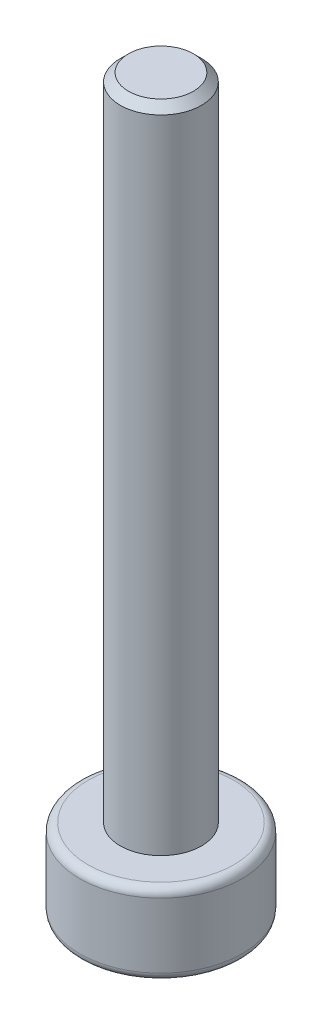
SolidWorks part; units mm, degrees
material "AISI 304"
ref_plane "前视基准面" through (0, 0, 0) normal (0, 0, 1) x (1, 0, 0)
ref_plane "上视基准面" through (0, 0, 0) normal (0, 1, 0) x (1, 0, 0)
ref_plane "右视基准面" through (0, 0, 0) normal (1, 0, 0) x (0, 0, -1)
sketch "草图2" plane through (0, 0, 0) normal (0, 1, 0) x (1, 0, 0)
  circle A0 centre (0, 0) radius 2
  dimension "D1" = 4
extrude "凸台-拉伸1" add sketch "草图2" along normal blind 2
sketch "草图3" plane through (0, 2, 0) normal (0, 1, 0) x (1, 0, 0)
  circle A0 centre (0, 0) radius 1
  dimension "D1" = 2
extrude "凸台-拉伸2" add sketch "草图3" along normal blind 16
fillet "圆角1" radius 0.2 2 edges at (0, 2, 2) (0, 0, 2)
sketch "草图4" plane through (0, 0, 0) normal (0, -1, 0) x (1, 0, 0)
  circle A0 centre (0, 0) radius 0.765
  dimension "D1" = 1.53
extrude "切除-拉伸1" cut sketch "草图4" against normal blind 1.52
chamfer "倒角1" distance 0.1 angle 45 1 edges at (0, 0, -0.765)
chamfer "倒角2" distance 0.2 angle 45 1 edges at (0, 18, 1)
